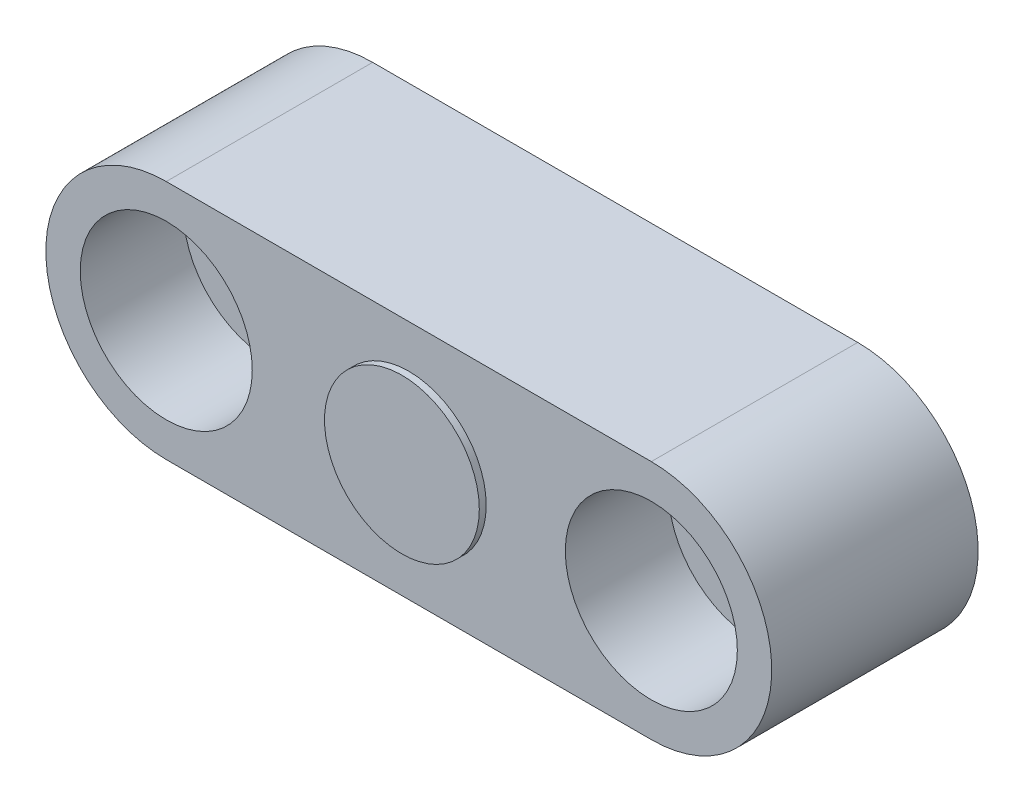
SolidWorks part; units mm, degrees
material "ABS PC"
ref_plane "Piano frontale" through (0, 0, 0) normal (0, 0, 1) x (1, 0, 0)
ref_plane "Piano superiore" through (0, 0, 0) normal (0, 1, 0) x (1, 0, 0)
ref_plane "Piano destro" through (0, 0, 0) normal (1, 0, 0) x (0, 0, -1)
sketch "Schizzo1" plane through (0, 0, 0) normal (0, 0, 1) x (1, 0, 0)
  line L0 (-7.05, 0) -> (7.05, 0) construction
  line L4 (7.05, -3.5) -> (-7.05, -3.5)
  line L7 (-7.05, 3.5) -> (7.05, 3.5)
  arc A2 (-7.05, 3.5) -> (-7.05, -3.5) centre (-7.05, 0) ccw
  arc A7 (7.05, 3.5) -> (7.05, -3.5) centre (7.05, 0) cw
  dimension "D3" = 7
  dimension "D1" = 14.1
extrude "Estrusione-Estrusione1" add sketch "Schizzo1" along normal blind 6
sketch "Schizzo2" plane through (0, 0, 6) normal (0, 0, 1) x (1, 0, 0)
  line L0 (-15.6186, 0) -> (15.6186, 0) construction
  line L1 (0, -7.8679) -> (0, 7.8679) construction
  circle A0 centre (7.05, 0) radius 2.5
  point P4 (0, 0)
  point P8 (0, 0)
  dimension "D1" = 5
extrude "Taglio-Estrusione1" cut sketch "Schizzo2" against normal blind 3
sketch "Schizzo3" plane through (0, 0, 3) normal (0, 0, 1) x (1, 0, 0)
  circle A0 centre (7.05, 0) radius 1.75
  dimension "D1" = 3.5
extrude "Taglio-Estrusione2" cut sketch "Schizzo3" against normal through all
sketch "Schizzo4" plane through (0, 0, 0) normal (0, 0, -1) x (-1, 0, 0)
  circle A2 centre (-7.05, 0) radius 2.5
  circle A3 centre (-7.05, 0) radius 2.5
  circle A5 centre (-7.05, 0) radius 1.75 construction
  circle A6 centre (-7.05, 0) radius 1.75
  dimension "D1" = 0
extrude "Taglio-Estrusione3" cut sketch "Schizzo4" against normal blind 2
mirror "Specchia1" about plane through (0, 0, 0) normal (1, 0, 0) of "Taglio-Estrusione3", "Taglio-Estrusione2", "Taglio-Estrusione1"
sketch "Schizzo6" plane through (0, 0, 0) normal (0, 0, -1) x (-1, 0, 0)
  line L0 (-5.4579, 2.75) -> (5.4579, 2.75)
  line L1 (-5.4579, -2.75) -> (5.4579, -2.75)
  line L2 (-7.05, 3.5) -> (7.05, 3.5) construction
  line L3 (0, 3.3) -> (0, -3.3) construction
  line L4 (7.05, -3.5) -> (-7.05, -3.5) construction
  circle A0 centre (-7.05, 0) radius 2.5 construction
  arc A4 (-5.4579, 2.75) -> (-5.4579, -2.75) centre (-7.05, 0) cw
  arc A6 (5.4579, 2.75) -> (5.4579, -2.75) centre (7.05, 0) ccw
  dimension "D3" = 3.1776
  dimension "D1" = 0.75
  dimension "D2" = 0.75
extrude "Taglio-Estrusione4" cut sketch "Schizzo6" against normal offset from surface (5 mm away) 1 up to face at (-9.55, 0, 6)
sketch "Schizzo5" plane through (0, 0, 6) normal (0, 0, 1) x (1, 0, 0)
  circle A0 centre (0, 0) radius 2.25
  dimension "D1" = 4.5
extrude "Estrusione-Estrusione2" add sketch "Schizzo5" along normal blind 0.2 and the other way blind 1.2
